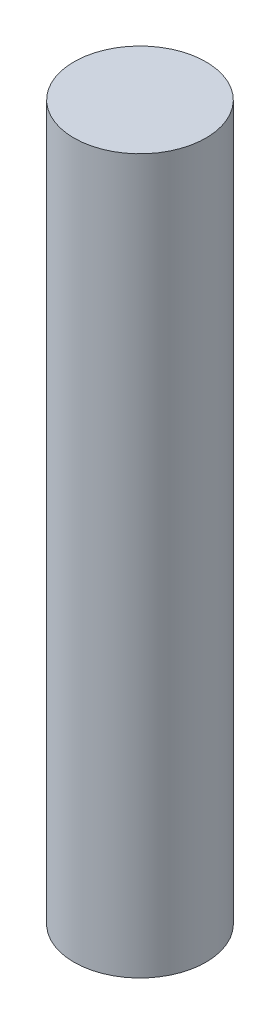
SolidWorks part; units mm, degrees
ref_plane "Front Plane" through (0, 0, 0) normal (0, 0, 1) x (1, 0, 0)
ref_plane "Top Plane" through (0, 0, 0) normal (0, 1, 0) x (1, 0, 0)
ref_plane "Right Plane" through (0, 0, 0) normal (1, 0, 0) x (0, 0, -1)
sketch "Sketch1" plane through (0, 0, 0) normal (0, 1, 0) x (1, 0, 0)
  circle A0 centre (0, 0) radius 0.925
  dimension "D1" = 1.85
extrude "Boss-Extrude1" add sketch "Sketch1" along normal blind 10
fillet "Fillet1" [suppressed] radius 0.5
